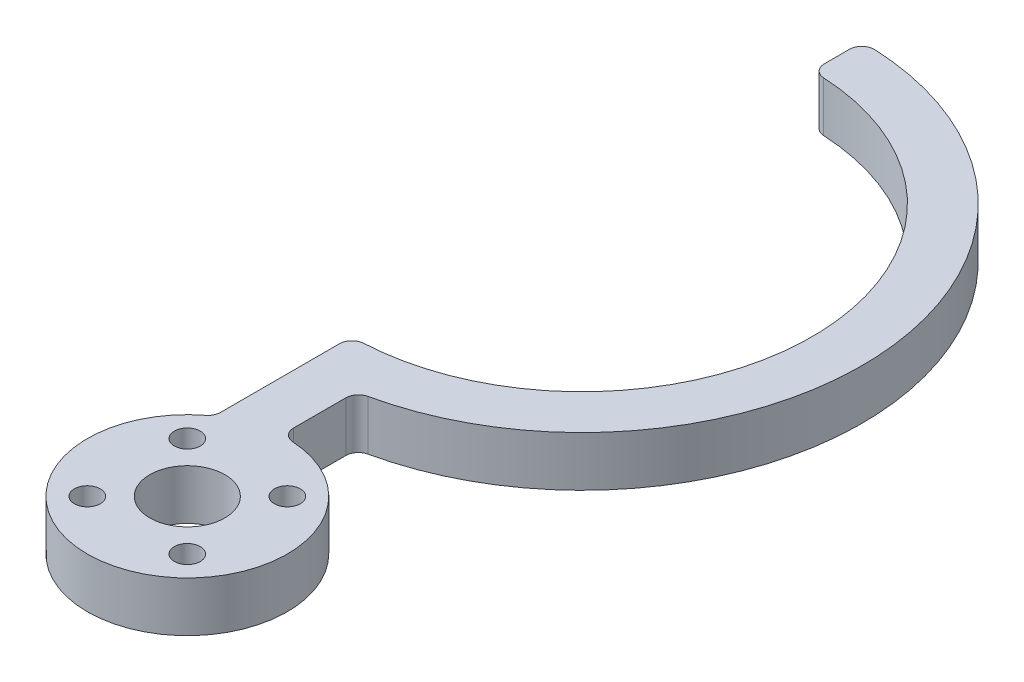
SolidWorks part; units mm, degrees
ref_plane "Front Plane" through (0, 0, 0) normal (0, 0, 1) x (1, 0, 0)
ref_plane "Top Plane" through (0, 0, 0) normal (0, 1, 0) x (1, 0, 0)
ref_plane "Right Plane" through (0, 0, 0) normal (1, 0, 0) x (0, 0, -1)
sketch "Sketch1" plane through (0, 0, 0) normal (0, 1, 0) x (1, 0, 0)
  line L0 (0, 44.83) -> (0, 36.83)
  line L1 (0, -36.83) -> (0, -46.83)
  line L2 (0, -46.83) -> (0, -58.83)
  line L3 (8, -44.1104) -> (8, -56.1104)
  line L8 (16.967, -80.0812) -> (0.967, -80.0812) construction
  line L13 (16.967, -80.0812) -> (16.967, -64.0812) construction
  line L21 (16.967, -64.0812) -> (0.967, -64.0812) construction
  line L22 (0.967, -80.0812) -> (0.967, -64.0812) construction
  line L23 (16.967, -80.0812) -> (0.967, -64.0812) construction
  line L24 (16.967, -64.0812) -> (0.967, -80.0812) construction
  arc A0 (0, -36.83) -> (0, 36.83) centre (0, 0) ccw
  arc A1 (8, -44.1104) -> (0, 44.83) centre (0, 0) ccw
  arc A7 (0, -58.83) -> (23.0776, -79.6236) centre (8.967, -72.0812) ccw
  circle A8 centre (0.967, -64.0812) radius 2.075
  circle A9 centre (16.967, -64.0812) radius 2.075
  circle A10 centre (16.967, -80.0812) radius 2.075
  circle A11 centre (0.967, -80.0812) radius 2.075
  arc A12 (0, -58.83) -> (8, -56.1104) centre (8.967, -72.0812) ccw
  circle A13 centre (8.967, -72.0812) radius 6.0032
  dimension "D1" = 73.66
  dimension "D8" = 4.15
  dimension "D6" = 16
  dimension "D2" = 8
  dimension "D3" = 8
  dimension "D4" = 12
  dimension "D9" = 10
  dimension "D7" = 16
  dimension "D5" = 12
extrude "Boss-Extrude2" add sketch "Sketch1" along normal blind 8 contours A7 A12 L3 A1 L0 A0 L1 L2 A8 A9 A10 A11
fillet "Fillet1" radius 2 6 edges at (0, 4, -36.83) (0, 4, -44.83) (8, 4, 56.1104) (8, 4, 44.1104) (0, 4, 58.83) (0, 4, 36.83)
equation "\"innerSmall\"= 2.9in"
equation "\"thick\"= 8mm"
equation "\"D1@Sketch1\"=\"innerSmall\""
equation "\"D2@Sketch1\"=\"thick\""
equation "\"D3@Sketch1\"=\"thick\""
equation "\"D7@Sketch1\"=16mm"
